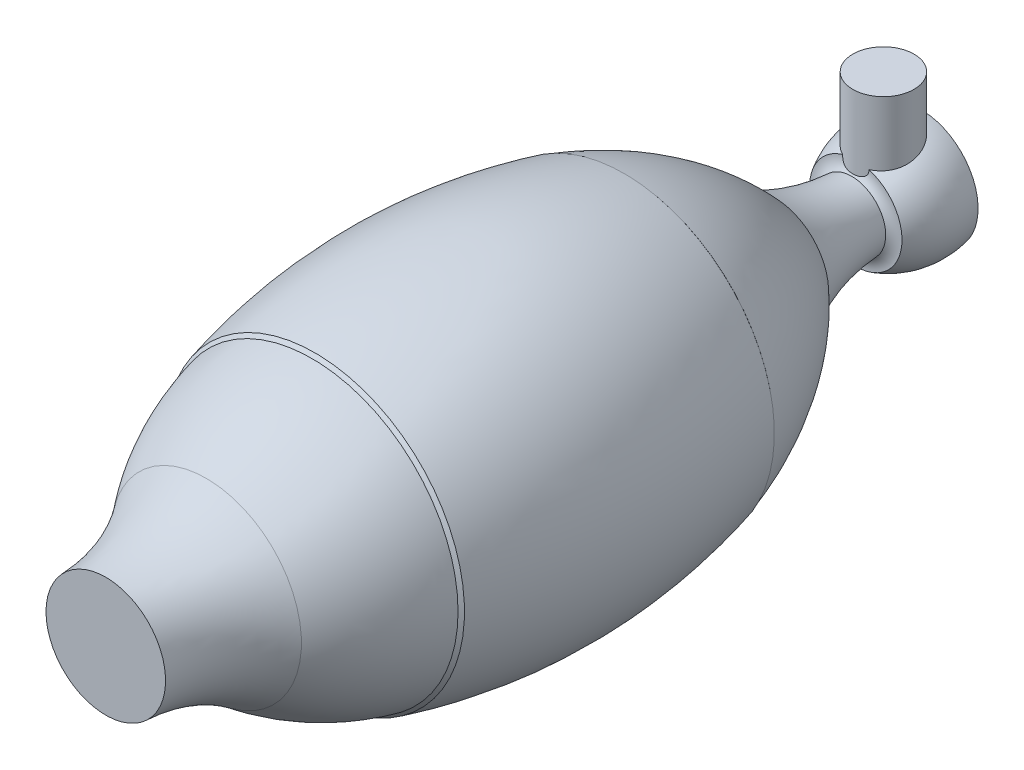
SolidWorks part; units mm, degrees
material "ABS PC"
ref_plane "Alzado" through (0, 0, 0) normal (0, 0, 1) x (1, 0, 0)
ref_plane "Planta" through (0, 0, 0) normal (0, 1, 0) x (1, 0, 0)
ref_plane "Vista lateral" through (0, 0, 0) normal (1, 0, 0) x (0, 0, -1)
sketch "Croquis2" plane through (0, 0, 0) normal (1, 0, 0) x (0, 0, -1)
  line L0 (150, 0) -> (-150, 0)
  line L1 (150, 0) -> (150, 21)
  line L2 (126, 0) -> (126, 17) construction
  line L3 (124.5, 0) -> (124.5, 12.5) construction
  line L4 (96, 0) -> (96, 20) construction
  line L5 (-113, 0) -> (-113, 35) construction
  line L6 (96, 0) -> (41, 0) construction
  line L7 (96, 0) -> (96, 55) construction
  line L8 (96, 55) -> (41, 55) construction
  line L9 (41, 0) -> (41, 55) construction
  line L10 (-150, 0) -> (-113, 0)
  line L11 (-150, 0) -> (-150, 22)
  line L12 (-150, 22) -> (-113, 22) construction
  line L13 (-113, 0) -> (-113, 22) construction
  line L14 (-21.015, 0) -> (-21.015, 62.5) construction
  line L15 (-113, 0) -> (-73, 0) construction
  line L16 (-113, 0) -> (-113, 55) construction
  line L17 (-113, 55) -> (-73, 55) construction
  line L18 (-73, 0) -> (-73, 55) construction
  line L19 (-74.1327, 53.7661) -> (-73, 55)
  line L20 (41, 55) -> (40.7927, 55.2388)
  spline S0 degree 2 poles (126, 17) (137.156, 23.4919) (150, 21) knots 0 0 0 1 1 1
  spline S1 degree 2 poles (124.5, 12.5) (126.0329, 14.4337) (126, 17) knots 0 0 0 1 1 1
  spline S2 degree 2 poles (96, 20) (109.457, 13.4163) (124.5, 12.5) knots 0 0 0 1 1 1
  spline S3 degree 2 poles (96, 20) (73.64, 44.7581) (41, 55) knots 0 0 0 1 1 1
  spline S4 degree 2 poles (-150, 22) (-129.3712, 22.8856) (-113, 35) knots 0 0 0 1 1 1
  spline S5 degree 2 poles (-113, 35) (-95.8818, 48.6467) (-74.1327, 53.7661) knots 0 0 0 1 1 1
  spline S6 degree 2 poles (-73, 55) (-16.2997, 70.0074) (40.7927, 55.2388) knots 0 0 0 1 1 1
  point P4 (0, 0)
  dimension "D1" = 300
  dimension "D2" = 21
  dimension "D3" = 24
  dimension "D4" = 17
  dimension "D5" = 12.5
  dimension "D6" = 1.5
  dimension "D7" = 20
  dimension "D8" = 30
  dimension "D9" = 55
  dimension "D10" = 55
  dimension "D11" = 22
  dimension "D12" = 37
  dimension "D13" = 35
  dimension "D14" = 55
  dimension "D15" = 40
  dimension "D16" = 62.5
revolve "Revolución1" add sketch "Croquis2" angle 360 about L0
sketch "Croquis3" plane through (0, 0, 0) normal (0, 1, 0) x (1, 0, 0)
  circle A0 centre (0, 136.1602) radius 11.2549
extrude "Saliente-Extruir1" add sketch "Croquis3" along normal blind 40
